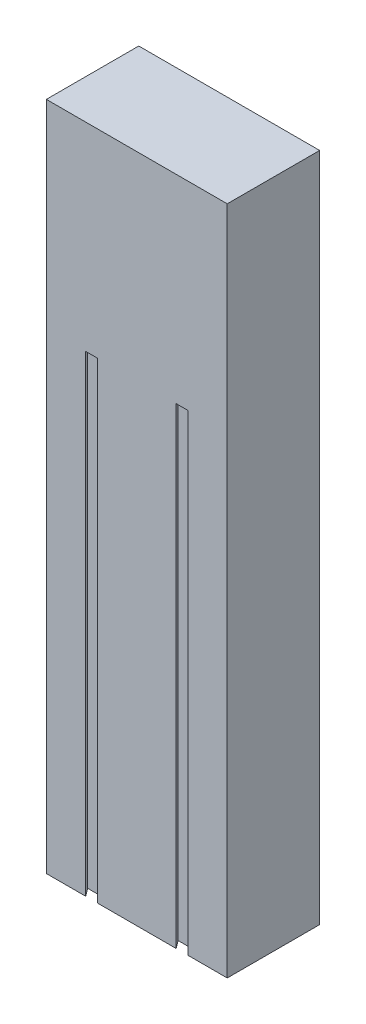
SolidWorks part; units mm, degrees
ref_plane "Přední rovina" through (0, 0, 0) normal (0, 0, 1) x (1, 0, 0)
ref_plane "Horní rovina" through (0, 0, 0) normal (0, 1, 0) x (1, 0, 0)
ref_plane "Pravá rovina" through (0, 0, 0) normal (1, 0, 0) x (0, 0, -1)
sketch "Skica1" plane through (0, 0, 0) normal (0, 0, 1) x (1, 0, 0)
  line L0 (1.1, 151.5) -> (0, 151.5) construction
  line L1 (0, 151.5) -> (34, 151.5)
  line L2 (0, 151.5) -> (0, 0)
  line L4 (34, 151.5) -> (34, 0)
  line L5 (0, 146) -> (0, 151.5) construction
  line L18 (-1.5, 153) -> (35.5, 153)
  line L20 (34, 0) -> (34, -7)
  line L21 (34, -7) -> (0, -7)
  line L22 (0, 0) -> (0, -7)
  line L23 (35.5, 153) -> (35.5, 0)
  line L24 (35.5, 0) -> (35.5, -8.5)
  line L25 (35.5, -8.5) -> (-1.5, -8.5)
  line L26 (-1.5, 0) -> (-1.5, -8.5)
  line L27 (-1.5, 153) -> (-1.5, 0)
  line L28 (-6, 157.5) -> (40, 157.5)
  line L29 (40, 157.5) -> (40, 0)
  line L30 (40, 0) -> (40, -13)
  line L31 (40, -13) -> (-6, -13)
  line L32 (-6, 0) -> (-6, -13)
  line L33 (-6, 157.5) -> (-6, 0)
  dimension "D3" = 7
  dimension "D1" = 1.5
  dimension "D2" = 6
extrude "Přidat vysunutím2" add sketch "Skica1" against normal up to surface (16.5 mm away)
sketch "Skica2" plane through (0, 0, 0) normal (0, 0, 1) x (1, 0, 0)
  line L1 (-6, 157.5) -> (40, 157.5)
  line L2 (-6, 157.5) -> (-6, -13)
  line L3 (-6, -13) -> (40, -13)
  line L4 (40, 157.5) -> (40, -13)
  line L5 (35.5, -8.5) -> (-1.5, -8.5)
  line L6 (35.5, -8.5) -> (35.5, 153)
  line L7 (35.5, 153) -> (-1.5, 153)
  line L8 (-1.5, -8.5) -> (-1.5, 153)
  point P12 (0, 0)
  point P14 (0, 0)
  point P16 (0, 0)
  point P18 (0, 0)
  point P19 (0, 0)
  point P20 (0, 0)
  point P21 (0, 0)
extrude "Přidat vysunutím4" add sketch "Skica2" along normal blind 2
sketch "Skica3" plane through (0, 0, 2) normal (0, 0, 1) x (1, 0, 0)
  line L0 (35.5, 119.5) -> (33.1, 119.5) construction
  line L1 (40, -13) -> (-6, -13)
  line L2 (40, -13) -> (40, 157.5)
  line L3 (40, 157.5) -> (-6, 157.5)
  line L4 (-6, -13) -> (-6, 157.5)
  line L5 (35.5, 119.5) -> (-1.5, 119.5)
  line L6 (35.5, 119.5) -> (35.5, 153)
  line L7 (35.5, 153) -> (-1.5, 153)
  line L8 (-1.5, 119.5) -> (-1.5, 153)
  line L9 (35.5, -8.5) -> (35.5, 153) construction
  line L10 (-6, 157.5) -> (-6, -13) construction
  line L11 (40, 157.5) -> (-6, 157.5) construction
  point P11 (0, 0)
  point P15 (0, 0)
  point P16 (0, 0)
  point P23 (0, 0)
  point P24 (-1.8112, 147.3333)
extrude "Přidat vysunutím5" add sketch "Skica3" along normal blind 3
sketch "Skica4" plane through (0, 0, 5) normal (0, 0, 1) x (1, 0, 0)
  line L1 (35.5, 119.5) -> (-1.5, 119.5)
  line L2 (35.5, 119.5) -> (35.5, 153)
  line L3 (35.5, 153) -> (-1.5, 153)
  line L4 (-1.5, 119.5) -> (-1.5, 153)
  point P6 (0, 0)
  point P7 (0, 0)
  point P8 (0, 0)
  point P10 (0, 0)
extrude "Přidat vysunutím6" add sketch "Skica4" against normal blind 2
sketch "Skica9" plane through (0, 0, -16.5) normal (0, 0, -1) x (-1, 0, 0)
  line L0 (1.5, 153) -> (1.5, -8.5) construction
  line L1 (-40, -13) -> (6, -13)
  line L2 (-40, -13) -> (-40, 157.5)
  line L3 (-40, 157.5) -> (6, 157.5)
  line L4 (6, -13) -> (6, 157.5)
  line L5 (1.5, 153) -> (-35.5, 153)
  line L6 (1.5, 153) -> (1.5, -8.5)
  line L7 (1.5, -8.5) -> (-35.5, -8.5)
  line L8 (-35.5, 153) -> (-35.5, -8.5)
  point P12 (0, 0)
  point P14 (0, 0)
  point P16 (1.5, 151.6903)
  point P20 (0, 0)
extrude "Přidat vysunutím9" add sketch "Skica9" along normal blind 2
sketch "Skica10" plane through (0, 0, -18.5) normal (0, 0, -1) x (-1, 0, 0)
  line L0 (-40, -13) -> (6, -13) construction
  line L1 (6, -13) -> (6, 157.5) construction
  line L2 (-17, -13) -> (-17, 0) construction
  line L3 (-40, -13) -> (-40, 72.25) construction
  line L4 (-40, 157.5) -> (-40, -13) construction
  line L5 (-40, 29.625) -> (-35.5, 29.625) construction
  line L6 (-35.5, 72.25) -> (-40, 72.25) construction
  line L7 (-35.5, 153) -> (-35.5, -8.5) construction
  line L8 (-35.5, 153) -> (-35.5, -8.5) construction
  line L9 (-37.75, 29.625) -> (-37.75, 72.25) construction
  line L10 (-37.75, 50.9375) -> (-40, 50.9375) construction
  line L11 (3.5, -10.5) -> (-37.5, -10.5) construction
  line L12 (3.5, -10.5) -> (3.5, 30.5) construction
  circle A0 centre (3.5, -10.5) radius 1.75
  circle A12 centre (-37.5, -10.5) radius 1.75
  circle A13 centre (-37.5, 30.5) radius 1.75
  circle A14 centre (-37.5, 71.5) radius 1.75
  circle A15 centre (-37.5, 112.5) radius 1.75
  circle A16 centre (-37.5, 153.5) radius 1.75
  circle A17 centre (3.5, 30.5) radius 1.75
  circle A18 centre (3.5, 71.5) radius 1.75
  circle A19 centre (3.5, 112.5) radius 1.75
  circle A20 centre (3.5, 153.5) radius 1.75
  dimension "D3" = 3.5
  dimension "D1" = 2.5
  dimension "D2" = 2.5
  dimension "D4" = 2
  dimension "D5" = 5
  dimension "D6" = 41
  dimension "D7" = 41
extrude "Díry na zápustný matky" cut sketch "Skica10" against normal blind 5
fillet "Zaoblit1" radius 2.5 4 edges at (35.5, 153, -7.75) (-1.5, 153, -7.75) (-1.5, -8.5, -8.25) (35.5, -8.5, -8.25)
sketch "Skica11" plane through (0, -13, 0) normal (0, -1, 0) x (1, 0, 0)
  line L0 (40, -18.5) -> (40, 5) construction
  line L1 (17, -18.5) -> (17, 5) construction
  line L2 (40, -18.5) -> (-6, -18.5) construction
  line L3 (-6, 5) -> (40, 5) construction
  circle A0 centre (27, -6.5) radius 5.75
  circle A1 centre (7, -6.5) radius 5.75
  dimension "D1" = 11.5
  dimension "D2" = 10
  dimension "D3" = 12
  dimension "D4" = 11.5
  dimension "D5" = 13
extrude "konektory" cut sketch "Skica11" against normal up to surface (4.5 mm away) up to face at (17, -8.5, -8.25)
sketch "Skica13" plane through (0, -13, 0) normal (0, -1, 0) x (1, 0, 0)
  line L0 (31.5, 3) -> (25.5, 3)
  line L1 (25.5, 3) -> (25.5, 5) construction
  line L2 (-6, 5) -> (40, 5) construction
  line L3 (31.5, 3) -> (31.5, 5) construction
  line L4 (30, 5) -> (27, 5) construction
  line L5 (30, 5) -> (31.5, 3)
  line L6 (25.5, 3) -> (27, 5)
  line L7 (27, 5) -> (30, 5)
  line L8 (17, 5) -> (17, -18.5) construction
  line L9 (7, 5) -> (4, 5)
  line L10 (4, 5) -> (2.5, 3)
  line L11 (8.5, 3) -> (7, 5)
  line L12 (2.5, 3) -> (8.5, 3)
  dimension "D1" = 6
  dimension "D2" = 2
  dimension "D3" = 3
  dimension "D4" = 1.5
  dimension "D5" = 1.5
  dimension "D6" = 10
  dimension "D7" = 10
  dimension "D8" = 20
extrude "Drážka k terču" cut sketch "Skica13" against normal blind 120
